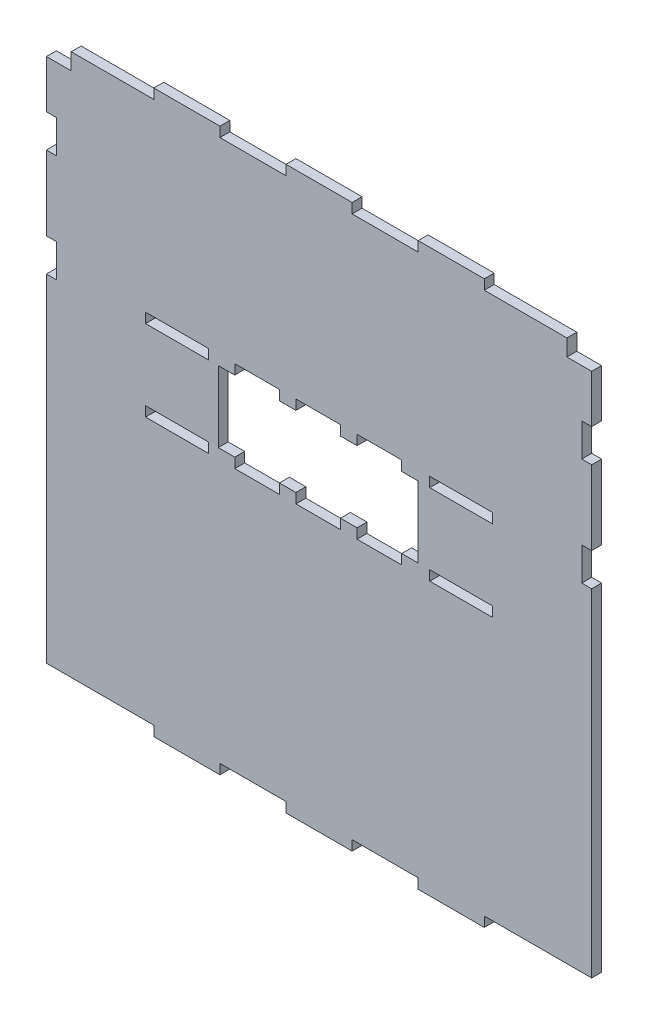
SolidWorks part; units mm, degrees
ref_plane "Plan de face" through (0, 0, 0) normal (0, 0, 1) x (1, 0, 0)
ref_plane "Plan de dessus" through (0, 0, 0) normal (0, 1, 0) x (1, 0, 0)
ref_plane "Plan de droite" through (0, 0, 0) normal (1, 0, 0) x (0, 0, -1)
sketch "Esquisse2" plane through (0, 0, 0) normal (0, 0, 1) x (1, 0, 0)
  line L1 (0, 0) -> (-330, 0)
  line L2 (0, 0) -> (0, -340)
  line L3 (0, -340) -> (-330, -340)
  line L4 (-330, 0) -> (-330, -340)
  dimension "D1" = 340
  dimension "D2" = 330
extrude "Boss.-Extru.1" add sketch "Esquisse2" along normal blind 6
sketch "Esquisse4" plane through (0, 0, 0) normal (0, 0, -1) x (-1, 0, 0)
  line L0 (0, 0) -> (330, 0) construction
  line L1 (330, 0) -> (265, 0)
  line L2 (330, 0) -> (330, -6)
  line L3 (330, -6) -> (265, -6)
  line L4 (265, 0) -> (265, -6)
  line L5 (225, 0) -> (185, 0)
  line L6 (225, 0) -> (225, -6)
  line L7 (225, -6) -> (185, -6)
  line L8 (185, 0) -> (185, -6)
  line L9 (330, 0) -> (330, -340) construction
  line L10 (145, 0) -> (105, 0)
  line L11 (145, 0) -> (145, -6)
  line L12 (145, -6) -> (105, -6)
  line L13 (105, 0) -> (105, -6)
  line L14 (0, 0) -> (65, 0)
  line L15 (0, 0) -> (0, -6)
  line L16 (0, -6) -> (65, -6)
  line L17 (65, 0) -> (65, -6)
  line L19 (330, -45) -> (324, -45)
  line L20 (330, -45) -> (330, -65)
  line L21 (330, -65) -> (324, -65)
  line L22 (330, -340) -> (0, -340) construction
  line L23 (324, -45) -> (324, -65)
  line L24 (0, -65) -> (6, -65)
  line L25 (0, -65) -> (0, -45)
  line L26 (0, -45) -> (6, -45)
  line L27 (330, -340) -> (265, -340)
  line L28 (330, -340) -> (330, -334)
  line L29 (330, -334) -> (265, -334)
  line L30 (265, -340) -> (265, -334)
  line L31 (225, -340) -> (185, -340)
  line L32 (225, -340) -> (225, -334)
  line L33 (225, -334) -> (185, -334)
  line L34 (185, -340) -> (185, -334)
  line L35 (0, -340) -> (0, 0) construction
  line L36 (145, -340) -> (105, -340)
  line L37 (145, -340) -> (145, -334)
  line L38 (145, -334) -> (105, -334)
  line L39 (105, -340) -> (105, -334)
  line L40 (65, -340) -> (0, -340)
  line L41 (65, -340) -> (65, -334)
  line L42 (65, -334) -> (0, -334)
  line L43 (0, -340) -> (0, -334)
  line L44 (330, -110) -> (324, -110)
  line L45 (330, -110) -> (330, -130)
  line L46 (330, -130) -> (324, -130)
  line L47 (324, -110) -> (324, -130)
  line L48 (6, -65) -> (6, -45)
  line L52 (0, -110) -> (6, -110)
  line L53 (0, -110) -> (0, -130)
  line L54 (0, -130) -> (6, -130)
  line L55 (6, -110) -> (6, -130)
  dimension "D1" = 6
  dimension "D2" = 65
  dimension "D3" = 40
  dimension "D4" = 6
  dimension "D5" = 40
  dimension "D6" = 40
  dimension "D7" = 6
  dimension "D8" = 40
  dimension "D9" = 40
  dimension "D10" = 6
  dimension "D11" = 20
  dimension "D12" = 6
  dimension "D13" = 45
  dimension "D14" = 45
  dimension "D15" = 65
  dimension "D16" = 6
  dimension "D17" = 6
  dimension "D18" = 40
  dimension "D19" = 40
  dimension "D20" = 40
  dimension "D21" = 40
  dimension "D22" = 6
  dimension "D23" = 65
  dimension "D24" = 40
  dimension "D25" = 6
  dimension "D26" = 20
  dimension "D27" = 20
  dimension "D28" = 45
  dimension "D29" = 45
  dimension "D30" = 6
  dimension "D31" = 6
  dimension "D32" = 20
  dimension "D34" = 6
extrude "Enlèv. mat encoche bord" cut sketch "Esquisse4" against normal through all
sketch "Esquisse5" plane through (0, 0, 0) normal (0, 0, -1) x (-1, 0, 0)
  line L1 (270, -175) -> (232, -175)
  line L2 (270, -175) -> (270, -169)
  line L3 (270, -169) -> (232, -169)
  line L4 (232, -175) -> (232, -169)
  line L5 (98, -175) -> (60, -175)
  line L6 (98, -175) -> (98, -169)
  line L7 (98, -169) -> (60, -169)
  line L8 (60, -175) -> (60, -169)
  line L9 (330, -6) -> (315, -6)
  line L10 (330, -6) -> (330, -16)
  line L11 (330, -16) -> (315, -16)
  line L12 (315, -6) -> (315, -16)
  line L13 (0, -6) -> (15, -6)
  line L14 (0, -6) -> (0, -16)
  line L15 (0, -16) -> (15, -16)
  line L16 (15, -6) -> (15, -16)
  line L17 (270, -126) -> (232, -126)
  line L18 (225, 0) -> (265, 0) construction
  line L19 (65, 0) -> (105, 0) construction
  line L20 (330, -130) -> (330, -334) construction
  line L21 (270, -126) -> (270, -120)
  line L22 (270, -120) -> (232, -120)
  line L23 (232, -126) -> (232, -120)
  line L24 (98, -126) -> (60, -126)
  line L25 (98, -126) -> (98, -120)
  line L26 (98, -120) -> (60, -120)
  line L27 (60, -126) -> (60, -120)
  dimension "D1" = 6
  dimension "D2" = 38
  dimension "D3" = 38
  dimension "D4" = 6
  dimension "D5" = 134
  dimension "D6" = 60
  dimension "D7" = 10
  dimension "D8" = 169
  dimension "D9" = 169
  dimension "D10" = 15
  dimension "D11" = 10
  dimension "D12" = 15
  dimension "D13" = 38
  dimension "D14" = 43
  dimension "D15" = 6
  dimension "D16" = 6
  dimension "D17" = 38
  dimension "D18" = 43
  dimension "D19" = 134
  dimension "D20" = 60
extrude "Enlèv. mat encoche étage + roulettes" cut sketch "Esquisse5" against normal through all
sketch "Esquisse6" plane through (0, 0, 0) normal (0, 0, -1) x (-1, 0, 0)
  line L1 (226, -169) -> (216, -169)
  line L2 (226, -169) -> (226, -126)
  line L3 (226, -126) -> (216, -126)
  line L4 (105, -169) -> (105, -126)
  line L6 (145, 0) -> (185, 0) construction
  line L8 (189, -169) -> (179, -169)
  line L9 (216, -175) -> (189, -175)
  line L10 (216, -175) -> (216, -169)
  line L11 (152, -169) -> (142, -169)
  line L12 (189, -175) -> (189, -169)
  line L13 (179, -175) -> (152, -175)
  line L14 (179, -175) -> (179, -169)
  line L15 (115, -169) -> (105, -169)
  line L16 (152, -175) -> (152, -169)
  line L17 (142, -175) -> (115, -175)
  line L18 (142, -175) -> (142, -169)
  line L19 (115, -126) -> (105, -126)
  line L20 (115, -175) -> (115, -169)
  line L22 (216, -126) -> (216, -120)
  line L23 (216, -120) -> (189, -120)
  line L24 (189, -126) -> (189, -120)
  line L25 (189, -126) -> (179, -126)
  line L26 (179, -126) -> (179, -120)
  line L27 (179, -120) -> (152, -120)
  line L28 (152, -126) -> (152, -120)
  line L29 (152, -126) -> (142, -126)
  line L30 (142, -126) -> (142, -120)
  line L31 (142, -120) -> (115, -120)
  line L32 (115, -126) -> (115, -120)
  line L33 (330, -130) -> (330, -334) construction
  line L34 (0, -334) -> (0, -130) construction
  dimension "D3" = 126
  dimension "D4" = 169
  dimension "D5" = 6
  dimension "D6" = 27
  dimension "D7" = 6
  dimension "D8" = 6
  dimension "D9" = 27
  dimension "D10" = 27
  dimension "D11" = 27
  dimension "D12" = 6
  dimension "D13" = 27
  dimension "D14" = 6
  dimension "D15" = 6
  dimension "D16" = 27
  dimension "D17" = 10
  dimension "D18" = 10
  dimension "D19" = 10
  dimension "D20" = 10
  dimension "D21" = 10
  dimension "D22" = 10
  dimension "D23" = 104
  dimension "D24" = 105
extrude "Enlèv. mat.-Extru.2" cut sketch "Esquisse6" against normal blind 6
